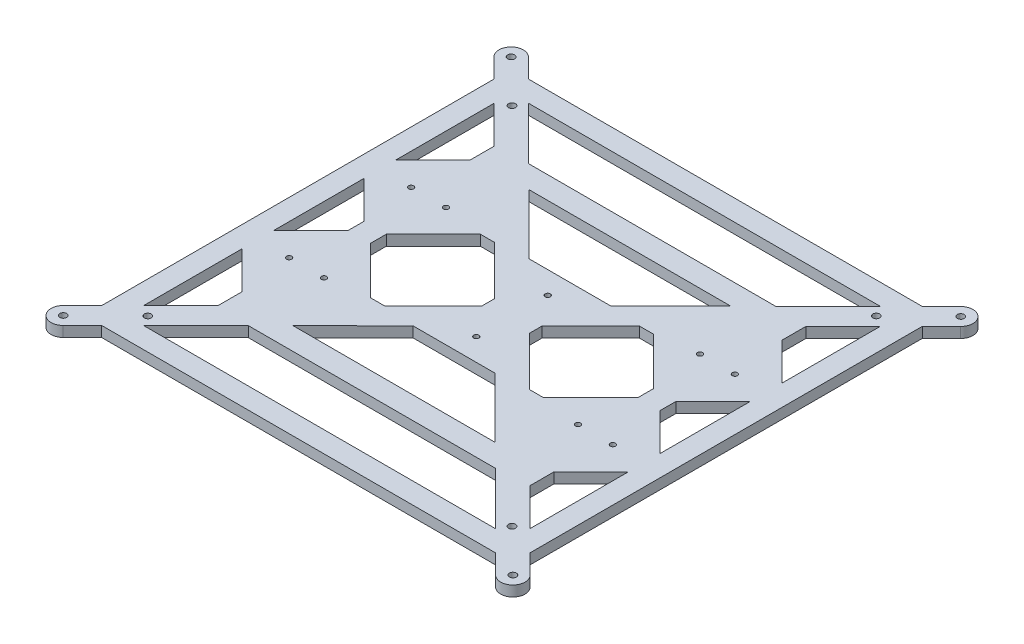
SolidWorks part; units mm, degrees
ref_plane "Plano frontal" through (0, 0, 0) normal (0, 0, 1) x (1, 0, 0)
ref_plane "Plano superior" through (0, 0, 0) normal (0, 1, 0) x (1, 0, 0)
ref_plane "Plano direito" through (0, 0, 0) normal (1, 0, 0) x (0, 0, -1)
sketch "Esboço1" plane through (0, 0, 0) normal (0, 1, 0) x (1, 0, 0)
  line L33 (0, 0) -> (0, 209) construction
  line L34 (104.5, 209) -> (104.5, 0) construction
  line L106 (-104.5, 104.5) -> (104.5, 104.5) construction
  line L107 (-104.5, 0) -> (104.5, 0) construction
  line L108 (0, 104.5) -> (104.5, 209) construction
  line L109 (0, 104.5) -> (104.5, 0) construction
  line L110 (99.9745, -4.5255) -> (71.3981, 24.051)
  line L111 (109.0255, 4.5255) -> (89.5, 24.051)
  line L112 (99.9745, 213.5255) -> (71.3981, 184.949)
  line L113 (109.0255, 204.4745) -> (89.5, 184.949)
  line L114 (82.9, 139.5) -> (82.9, 69.5) construction
  line L115 (72.9, 139.5) -> (92.9, 139.5) construction
  line L120 (72.9, 69.5) -> (92.9, 69.5) construction
  line L121 (71.3981, 24.051) -> (89.5, 24.051) construction
  line L122 (89.5, 184.949) -> (89.5, 24.051) construction
  line L123 (71.3981, 184.949) -> (89.5, 184.949) construction
  line L124 (89.5, 184.949) -> (89.5, 169.949)
  line L125 (71.3981, 184.949) -> (-71.3981, 184.949)
  line L126 (89.5, 169.949) -> (102.5, 156.949)
  line L127 (102.5, 156.949) -> (102.5, 122.051)
  line L128 (102.5, 122.051) -> (89.5, 109.051)
  line L129 (89.5, 109.051) -> (89.5, 99.949)
  line L130 (89.5, 99.949) -> (102.5, 86.949)
  line L131 (102.5, 86.949) -> (102.5, 52.051)
  line L132 (102.5, 52.051) -> (89.5, 39.051)
  line L133 (89.5, 39.051) -> (89.5, 24.051)
  line L135 (71.3981, 24.051) -> (-71.3981, 24.051)
  line L136 (-58.5981, 172.149) -> (58.5981, 172.149)
  line L137 (58.5981, 172.149) -> (24.249, 137.8)
  line L138 (24.249, 137.8) -> (-24.249, 137.8)
  line L139 (40.601, 136.05) -> (13.6019, 109.051)
  line L141 (13.6019, 109.051) -> (13.6019, 99.949)
  line L143 (40.601, 136.05) -> (49.701, 136.05)
  line L145 (49.701, 136.05) -> (76.7, 109.051)
  line L147 (76.7, 109.051) -> (76.7, 99.949)
  line L148 (76.7, 99.949) -> (49.701, 72.95)
  line L149 (49.701, 72.95) -> (40.601, 72.95)
  line L150 (40.601, 72.95) -> (13.6019, 99.949)
  line L151 (-58.5981, 36.851) -> (58.5981, 36.851)
  line L152 (58.5981, 36.851) -> (24.249, 71.2)
  line L153 (24.249, 71.2) -> (-24.249, 71.2)
  line L155 (-71.3981, 184.949) -> (-89.5, 184.949) construction
  line L156 (-89.5, 184.949) -> (-89.5, 24.051) construction
  line L157 (-71.3981, 24.051) -> (-89.5, 24.051) construction
  line L158 (-72.9, 69.5) -> (-92.9, 69.5) construction
  line L159 (-72.9, 139.5) -> (-92.9, 139.5) construction
  line L160 (-82.9, 139.5) -> (-82.9, 69.5) construction
  line L161 (0, 104.5) -> (-104.5, 0) construction
  line L162 (0, 104.5) -> (-104.5, 209) construction
  line L163 (-104.5, 209) -> (-104.5, 0) construction
  line L165 (-58.5981, 36.851) -> (-24.249, 71.2)
  line L167 (-40.601, 72.95) -> (-13.6019, 99.949)
  line L168 (-49.701, 72.95) -> (-40.601, 72.95)
  line L169 (-76.7, 99.949) -> (-49.701, 72.95)
  line L170 (-76.7, 109.051) -> (-76.7, 99.949)
  line L171 (-49.701, 136.05) -> (-76.7, 109.051)
  line L172 (-40.601, 136.05) -> (-49.701, 136.05)
  line L173 (-13.6019, 109.051) -> (-13.6019, 99.949)
  line L174 (-40.601, 136.05) -> (-13.6019, 109.051)
  line L176 (-58.5981, 172.149) -> (-24.249, 137.8)
  line L179 (-89.5, 39.051) -> (-89.5, 24.051)
  line L180 (-102.5, 52.051) -> (-89.5, 39.051)
  line L181 (-102.5, 86.949) -> (-102.5, 52.051)
  line L182 (-89.5, 99.949) -> (-102.5, 86.949)
  line L183 (-89.5, 109.051) -> (-89.5, 99.949)
  line L184 (-102.5, 122.051) -> (-89.5, 109.051)
  line L185 (-102.5, 156.949) -> (-102.5, 122.051)
  line L186 (-89.5, 169.949) -> (-102.5, 156.949)
  line L188 (-89.5, 184.949) -> (-89.5, 169.949)
  line L189 (-109.0255, 204.4745) -> (-89.5, 184.949)
  line L190 (-99.9745, 213.5255) -> (-71.3981, 184.949)
  line L191 (-109.0255, 4.5255) -> (-89.5, 24.051)
  line L192 (-99.9745, -4.5255) -> (-71.3981, 24.051)
  circle A18 centre (104.5, 209) radius 2
  circle A20 centre (104.5, 0) radius 2
  arc A43 (109.0255, 204.4745) -> (99.9745, 213.5255) centre (104.5, 209) ccw
  arc A44 (99.9745, -4.5255) -> (109.0255, 4.5255) centre (104.5, 0) ccw
  circle A46 centre (0, 125) radius 1.5
  circle A47 centre (0, 84) radius 1.5
  circle A48 centre (72.9, 139.5) radius 1.5
  circle A49 centre (92.9, 139.5) radius 1.5
  circle A50 centre (72.9, 69.5) radius 1.5
  circle A51 centre (92.9, 69.5) radius 1.5
  circle A52 centre (-92.9, 69.5) radius 1.5
  circle A53 centre (-72.9, 69.5) radius 1.5
  circle A54 centre (-92.9, 139.5) radius 1.5
  circle A55 centre (-72.9, 139.5) radius 1.5
  arc A56 (-99.9745, -4.5255) -> (-109.0255, 4.5255) centre (-104.5, 0) cw
  arc A57 (-109.0255, 204.4745) -> (-99.9745, 213.5255) centre (-104.5, 209) cw
  circle A58 centre (-104.5, 0) radius 2
  circle A59 centre (-104.5, 209) radius 2
  point P12 (82.9, 104.5)
  point P21 (82.9, 139.5)
  point P26 (82.9, 69.5)
  point P31 (102.5, 139.5)
  point P45 (102.5, 69.5)
  point P46 (0, 24.051)
  point P53 (13.6019, 104.5)
  point P60 (76.7, 104.5)
  point P87 (0, 71.2)
  point P88 (0, 36.851)
  point P97 (0, 137.8)
  point P98 (0, 172.149)
  point P106 (0, 184.949)
  dimension "D2" = 4
  dimension "D4" = 4.4
  dimension "D7" = 3
  dimension "D12" = 3
  dimension "D1" = 209
  dimension "D3" = 104.5
  dimension "D5" = 82.9
  dimension "D6" = 70
  dimension "D8" = 20.5
  dimension "D9" = 20.5
  dimension "D10" = 20
  dimension "D11" = 20
  dimension "D13" = 15
  dimension "D14" = 15
  dimension "D15" = 13
  dimension "D16" = 45
  dimension "D17" = 45
  dimension "D18" = 13
  dimension "D19" = 45
  dimension "D20" = 15
  dimension "D21" = 12.8
  dimension "D22" = 12.8
  dimension "D23" = 12.8
  dimension "D24" = 45
  dimension "D25" = 9.1
  dimension "D26" = 9.1
  dimension "D27" = 12.8
  dimension "D28" = 12.8
extrude "Ressalto-extrusão1" add sketch "Esboço1" along normal blind 6 contours A57 L189 L188 L186 L185 L184 L183 L182 L181 L180 L179 L191 A56 L192 L135 L110 A44 L111 L133 L132 L131 L130 L129 L128 L127 L126 L124 L113 A43 L112 L125 L190 A58 A54 A52 A51 A50 A49 A48 A47 A46
sketch "Esboço2" plane through (0, 6, 0) normal (0, 1, 0) x (1, 0, 0)
  line L0 (-13.6019, 104.5) -> (13.6019, 104.5) construction
  line L1 (-13.6019, 109.051) -> (-13.6019, 99.949) construction
  line L2 (13.6019, 109.051) -> (13.6019, 99.949) construction
  line L3 (-133.9401, 228.0407) -> (-9.9188, 104.5)
  line L4 (-129, 233) -> (129, 233) construction
  line L5 (-129, 233) -> (-129, -24) construction
  line L6 (-129, -24) -> (129, -24) construction
  line L7 (129, 233) -> (129, -24) construction
  line L8 (-129, 233) -> (129, -24) construction
  line L9 (-129, -24) -> (129, 233) construction
  line L10 (-124.0599, -28.9593) -> (0, 94.6197)
  line L11 (-124.0599, 237.9593) -> (0, 114.3803)
  line L12 (-133.9401, -19.0407) -> (-9.9188, 104.5)
  line L13 (9.9188, 104.5) -> (133.9401, -19.0407)
  line L14 (-124.0599, 237.9593) -> (133.9401, -19.0407) construction
  line L15 (0, 114.3803) -> (124.0599, 237.9593)
  line L16 (-133.9401, -19.0407) -> (124.0599, 237.9593) construction
  line L17 (9.9188, 104.5) -> (133.9401, 228.0407)
  line L18 (-124.0599, -28.9593) -> (133.9401, 228.0407) construction
  line L19 (0, 94.6197) -> (124.0599, -28.9593)
  line L20 (-133.9401, 228.0407) -> (124.0599, -28.9593) construction
  line L22 (-120, 219.5) -> (120, 219.5) construction
  line L23 (-120, 219.5) -> (-120, -10.5) construction
  line L24 (-120, -10.5) -> (120, -10.5) construction
  line L25 (120, 219.5) -> (120, -10.5) construction
  line L26 (-120, 219.5) -> (120, -10.5) construction
  line L27 (-120, -10.5) -> (120, 219.5) construction
  circle A0 centre (-129, 233) radius 2
  circle A1 centre (129, 233) radius 2
  circle A2 centre (129, -24) radius 2
  circle A3 centre (-129, -24) radius 2
  arc A4 (-133.9401, 228.0407) -> (-124.0599, 237.9593) centre (-129, 233) cw
  arc A5 (124.0599, -28.9593) -> (133.9401, -19.0407) centre (129, -24) ccw
  arc A6 (-124.0599, -28.9593) -> (-133.9401, -19.0407) centre (-129, -24) cw
  arc A7 (133.9401, 228.0407) -> (124.0599, 237.9593) centre (129, 233) ccw
  circle A8 centre (104.5, 0) radius 2 construction
  circle A9 centre (-104.5, 0) radius 2 construction
  circle A10 centre (104.5, 209) radius 2 construction
  circle A11 centre (-104.5, 209) radius 2 construction
  circle A12 centre (104.5, 0) radius 2
  circle A13 centre (-104.5, 0) radius 2
  circle A14 centre (104.5, 209) radius 2
  circle A15 centre (-104.5, 209) radius 2
  point P6 (0, 104.5)
  point P24 (0, 104.5)
  dimension "D3" = 4
  dimension "D1" = 258
  dimension "D2" = 257
  dimension "D6" = 240
  dimension "D7" = 230
  dimension "D4" = 7
  dimension "D5" = 7
extrude "Ressalto-extrusão2" add sketch "Esboço2" against normal up to surface (6 mm away) up to face at (-104.5, 0, 2)
sketch "Esboço3" plane through (0, 6, 0) normal (0, 1, 0) x (1, 0, 0)
  line L0 (0, 0) -> (0, 239.6702) construction
sketch "Esboço4" plane through (0, 6, 0) normal (0, 1, 0) x (1, 0, 0)
  line L0 (-113.0067, 226.949) -> (113.0067, 226.949)
  line L1 (-70.8433, 184.949) -> (-124.0599, 237.9593) construction
  line L2 (124.0599, 237.9593) -> (70.8433, 184.949) construction
  line L3 (-100.96, 214.949) -> (100.96, 214.949)
  line L4 (100.96, 214.949) -> (113.0067, 226.949)
  line L5 (-113.0067, 226.949) -> (-100.96, 214.949)
  line L7 (70.8433, 184.949) -> (-70.8433, 184.949) construction
  line L8 (-13.6019, 104.5) -> (13.6019, 104.5) construction
  line L9 (-13.6019, 108.1689) -> (-13.6019, 100.8311) construction
  line L10 (13.6019, 108.1689) -> (13.6019, 100.8311) construction
  line L11 (-113.0067, -17.949) -> (113.0067, -17.949)
  line L12 (100.96, -5.949) -> (113.0067, -17.949)
  line L13 (-100.96, -5.949) -> (100.96, -5.949)
  line L14 (-113.0067, -17.949) -> (-100.96, -5.949)
  line L15 (-113.0067, 226.949) -> (-122.887, 217.0303) construction
  line L16 (-133.9401, 228.0407) -> (-89.5, 183.7728) construction
  line L17 (-122.887, 217.0303) -> (-122.887, -8.0303)
  line L18 (-89.5, 25.2272) -> (-133.9401, -19.0407) construction
  line L19 (-100.96, 214.949) -> (-110.8403, 205.0303) construction
  line L20 (-110.8403, 205.0303) -> (-110.8403, 148.6088)
  line L21 (-110.8403, 205.0303) -> (-122.887, 217.0303)
  line L22 (-110.8403, 3.9697) -> (-122.887, -8.0303)
  line L23 (0, 71.2) -> (0, 137.8) construction
  line L24 (23.5108, 71.2) -> (-23.5108, 71.2) construction
  line L25 (23.5108, 137.8) -> (-23.5108, 137.8) construction
  line L26 (-102.5, 156.949) -> (-110.8403, 148.6088)
  line L27 (-89.5, 169.949) -> (-102.5, 156.949) construction
  line L28 (-102.5, 122.051) -> (-110.8403, 130.3912)
  line L29 (-102.5, 122.051) -> (-89.5, 109.051) construction
  line L30 (-110.8403, 130.3912) -> (-110.8403, 78.6088)
  line L31 (-102.5, 156.949) -> (-102.5, 122.051)
  line L32 (-102.5, 86.949) -> (-110.8403, 78.6088)
  line L33 (-102.5, 52.051) -> (-110.8403, 60.3912)
  line L34 (-102.5, 52.051) -> (-89.5, 39.051) construction
  line L35 (-89.5, 99.949) -> (-102.5, 86.949) construction
  line L36 (-110.8403, 60.3912) -> (-110.8403, 3.9697)
  line L37 (-102.5, 86.949) -> (-102.5, 52.051)
  line L38 (102.5, 86.949) -> (110.8403, 78.6088)
  line L39 (110.8403, 130.3912) -> (110.8403, 78.6088)
  line L40 (102.5, 122.051) -> (110.8403, 130.3912)
  line L41 (102.5, 156.949) -> (102.5, 122.051)
  line L42 (102.5, 156.949) -> (110.8403, 148.6088)
  line L43 (110.8403, 205.0303) -> (110.8403, 148.6088)
  line L44 (110.8403, 205.0303) -> (122.887, 217.0303)
  line L45 (122.887, 217.0303) -> (122.887, -8.0303)
  line L46 (110.8403, 3.9697) -> (122.887, -8.0303)
  line L47 (110.8403, 60.3912) -> (110.8403, 3.9697)
  line L48 (102.5, 52.051) -> (110.8403, 60.3912)
  line L49 (102.5, 86.949) -> (102.5, 52.051)
  dimension "D1" = 12
  dimension "D2" = 30
extrude "Ressalto-extrusão4" add sketch "Esboço4" against normal up to surface (6 mm away) contours L38 L49 L48 L47 L46 L45 L44 L43 L42 L41 L40 L39 | L0 L5 L3 L4 | L30 L32 L37 L33 L36 L22 L17 L21 L20 L26 L31 L28 | L13 L12 L11 L14 up to face at (-45.3986, 0, -104.5)
